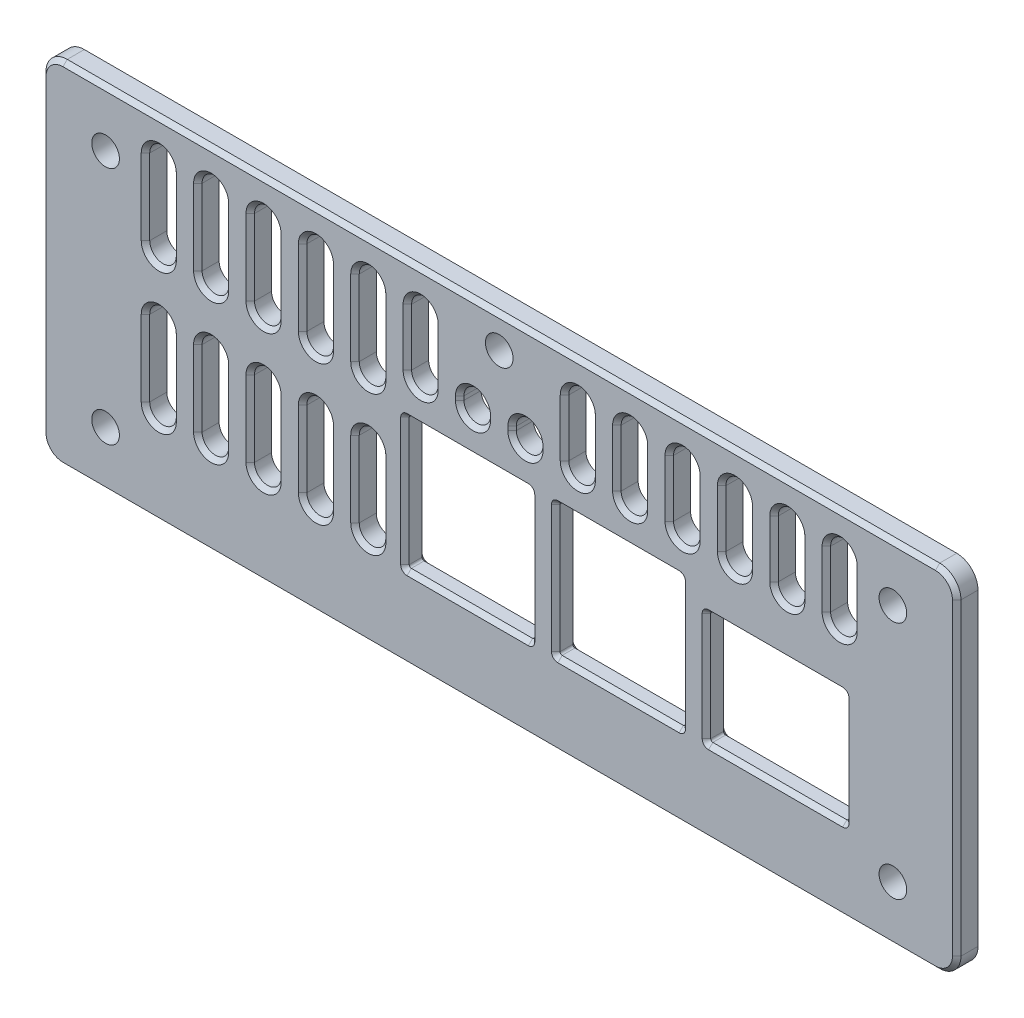
SolidWorks part; units mm, degrees
ref_plane "Plane XZ" through (0, 0, 0) normal (0, 0, 1) x (1, 0, 0)
ref_plane "Plane XY" through (0, 0, 0) normal (0, 1, 0) x (1, 0, 0)
ref_plane "Plane YZ" through (0, 0, 0) normal (1, 0, 0) x (0, 0, -1)
sketch "Sketch1" plane through (0, 0, 0) normal (0, 0, 1) x (1, 0, 0)
  line L0 (-55.88, -14.2875) -> (55.88, -14.2875) construction
  line L1 (-55.88, 22.225) -> (55.88, 22.225) construction
  line L2 (-55.88, 22.225) -> (-55.88, -22.225) construction
  line L3 (-55.88, -22.225) -> (55.88, -22.225) construction
  line L4 (55.88, 22.225) -> (55.88, -22.225) construction
  line L5 (0, 0) -> (0, -14.2875) construction
  line L6 (0, 0) -> (-55.88, 0) construction
  line L7 (-54.61, 20.955) -> (54.61, 20.955)
  line L8 (54.61, 20.955) -> (54.61, -20.955)
  line L9 (-54.61, -20.955) -> (54.61, -20.955)
  line L10 (-54.61, 20.955) -> (-54.61, -20.955)
  dimension "D1" = 111.76
  dimension "D2" = 44.45
  dimension "D3" = 14.2875
  dimension "D4" = 1.27
extrude "Boss-Extrude1" add sketch "Sketch1" along normal blind 2.54
sketch "Sketch4" plane through (0, 0, 2.54) normal (0, 0, 1) x (1, 0, 0)
  line L0 (-46.99, 0) -> (46.99, 0) construction
  line L1 (-46.99, 14.2875) -> (46.99, 14.2875) construction
  line L2 (-46.99, 14.2875) -> (-46.99, -14.2875) construction
  line L3 (-46.99, -14.2875) -> (46.99, -14.2875) construction
  line L4 (46.99, 14.2875) -> (46.99, -14.2875) construction
  circle A0 centre (-46.99, 14.2875) radius 1.651
  circle A1 centre (-46.99, -14.2875) radius 1.651
  circle A2 centre (46.99, -14.2875) radius 1.651
  circle A3 centre (46.99, 14.2875) radius 1.651
  dimension "D1" = 3.302
  dimension "D4" = 3.302
  dimension "D2" = 93.98
  dimension "D3" = 28.575
extrude "Cut-Extrude2" cut sketch "Sketch4" against normal through all and the other way through all
fillet "Fillet1" radius 2.54 4 edges at (54.61, 20.955, 1.27) (54.61, -20.955, 1.27) (-54.61, -20.955, 1.27) (-54.61, 20.955, 1.27)
sketch "Sketch3" plane through (0, 0, 2.54) normal (0, 0, 1) x (1, 0, 0)
  line L0 (15.24, -11.1252) -> (15.24, -12.3825) construction
  line L1 (-12.76, -11.1252) -> (43.24, -11.1252) construction
  line L2 (-12.76, -11.1252) -> (-12.76, -12.3825) construction
  line L3 (-12.76, -12.3825) -> (43.24, -12.3825) construction
  line L4 (43.24, -11.1252) -> (43.24, -12.3825) construction
  line L5 (-55.88, -14.2875) -> (55.88, -14.2875) construction
  line L6 (-3.76, 4.6228) -> (-3.76, -11.1252) construction
  line L7 (-11.253, 4.6228) -> (3.733, 4.6228)
  line L8 (-11.253, 4.6228) -> (-11.253, -11.1252)
  line L9 (-11.253, -11.1252) -> (3.733, -11.1252)
  line L10 (3.733, 4.6228) -> (3.733, -11.1252)
  line L11 (6.747, 4.6228) -> (21.733, 4.6228)
  line L12 (6.747, 4.6228) -> (6.747, -11.1252)
  line L13 (6.747, -11.1252) -> (21.733, -11.1252)
  line L14 (21.733, 4.6228) -> (21.733, -11.1252)
  line L15 (24.735, 2.3368) -> (41.245, 2.3368)
  line L16 (24.735, 2.3368) -> (24.735, -11.1252)
  line L17 (24.735, -11.1252) -> (41.245, -11.1252)
  line L18 (41.245, 2.3368) -> (41.245, -11.1252)
  line L19 (14.24, 4.6228) -> (14.24, -11.1252) construction
  line L20 (32.99, 2.3368) -> (32.99, -11.1252) construction
  dimension "D1" = 15.24
  dimension "D2" = 1.905
  dimension "D3" = 1.2573
  dimension "D4" = 56
  dimension "D5" = 15.748
  dimension "D6" = 14.986
  dimension "D7" = 16.51
  dimension "D8" = 13.462
  dimension "D9" = 9
  dimension "D10" = 27
  dimension "D11" = 45.75
extrude "RPi 4 Cutout" cut sketch "Sketch3" against normal through all
sketch "Sketch14" plane through (0, 0, 2.54) normal (0, 0, 1) x (1, 0, 0)
  circle A0 centre (0, 17.145) radius 1.651
  dimension "D2" = 3.302
  dimension "D1" = 17.145
extrude "Cut-Extrude8" cut sketch "Sketch14" against normal through all
sketch "Sketch15" plane through (0, 0, 2.54) normal (0, 0, 1) x (1, 0, 0)
  line L0 (40.64, 9.3853) -> (40.64, 16.1925) construction
  line L1 (54.61, 0) -> (50.3635, 0) construction
  line L2 (50.3635, -17.78) -> (-15.1531, -17.78) construction
  line L3 (50.3635, -17.78) -> (50.3635, 17.78) construction
  line L4 (50.3635, 17.78) -> (-15.1531, 17.78) construction
  line L5 (-15.1531, -17.78) -> (-15.1531, 17.78) construction
  line L6 (54.61, -18.415) -> (54.61, 18.415) construction
  line L7 (39.0525, 9.3853) -> (39.0525, 16.1925)
  line L8 (42.2275, 9.3853) -> (42.2275, 16.1925)
  line L9 (-15.1531, 7.7978) -> (50.3635, 7.7978) construction
  line L10 (21.733, 4.6228) -> (6.747, 4.6228) construction
  line L11 (34.3877, 9.3853) -> (34.3877, 16.1925) construction
  line L12 (32.8002, 9.3853) -> (32.8002, 16.1925)
  line L13 (35.9752, 9.3853) -> (35.9752, 16.1925)
  line L14 (28.1354, 9.3853) -> (28.1354, 16.1925) construction
  line L15 (26.5479, 9.3853) -> (26.5479, 16.1925)
  line L16 (29.7229, 9.3853) -> (29.7229, 16.1925)
  line L17 (21.8831, 9.3853) -> (21.8831, 16.1925) construction
  line L18 (20.2956, 9.3853) -> (20.2956, 16.1925)
  line L19 (23.4706, 9.3853) -> (23.4706, 16.1925)
  line L20 (15.6308, 9.3853) -> (15.6308, 16.1925) construction
  line L21 (14.0433, 9.3853) -> (14.0433, 16.1925)
  line L22 (17.2183, 9.3853) -> (17.2183, 16.1925)
  line L23 (9.3785, 9.3853) -> (9.3785, 16.1925) construction
  line L24 (7.791, 9.3853) -> (7.791, 16.1925)
  line L25 (10.966, 9.3853) -> (10.966, 16.1925)
  line L26 (3.1262, 9.3853) -> (3.1262, 16.1925) construction
  line L27 (1.5387, 9.3853) -> (1.5387, 16.1925) construction
  line L28 (4.7137, 9.3853) -> (4.7137, 16.1925) construction
  line L29 (-3.1262, 9.3853) -> (-3.1262, 16.1925) construction
  line L30 (-4.7137, 9.3853) -> (-4.7137, 16.1925) construction
  line L31 (-1.5387, 9.3853) -> (-1.5387, 16.1925) construction
  line L32 (-9.3785, 9.3853) -> (-9.3785, 16.1925) construction
  line L33 (-10.966, 9.3853) -> (-10.966, 16.1925)
  line L34 (-7.791, 9.3853) -> (-7.791, 16.1925)
  line L35 (-3.1262, 9.3853) -> (-3.1262, 9.849) construction
  line L36 (-4.7137, 9.3853) -> (-4.7137, 9.849)
  line L37 (-1.5387, 9.3853) -> (-1.5387, 9.849)
  line L38 (3.1262, 9.3853) -> (3.1262, 9.849) construction
  line L39 (1.5387, 9.3853) -> (1.5387, 9.849)
  line L40 (4.7137, 9.3853) -> (4.7137, 9.849)
  line L41 (-15.6308, 9.3853) -> (-15.6308, 16.1925) construction
  line L42 (-17.2183, 9.3853) -> (-17.2183, 16.1925)
  line L43 (-14.0433, 9.3853) -> (-14.0433, 16.1925)
  line L44 (-21.8831, 9.3853) -> (-21.8831, 16.1925) construction
  line L45 (-23.4706, 9.3853) -> (-23.4706, 16.1925)
  line L46 (-20.2956, 9.3853) -> (-20.2956, 16.1925)
  line L47 (-28.1354, 9.3853) -> (-28.1354, 16.1925) construction
  line L48 (-29.7229, 9.3853) -> (-29.7229, 16.1925)
  line L49 (-26.5479, 9.3853) -> (-26.5479, 16.1925)
  line L50 (-34.3877, 9.3853) -> (-34.3877, 16.1925) construction
  line L51 (-35.9752, 9.3853) -> (-35.9752, 16.1925)
  line L52 (-32.8002, 9.3853) -> (-32.8002, 16.1925)
  line L53 (-40.64, 9.3853) -> (-40.64, 16.1925) construction
  line L54 (-42.2275, 9.3853) -> (-42.2275, 16.1925)
  line L55 (-39.0525, 9.3853) -> (-39.0525, 16.1925)
  circle A0 centre (46.99, 14.2875) radius 4.7625 construction
  arc A1 (39.0525, 9.3853) -> (42.2275, 9.3853) centre (40.64, 9.3853) ccw
  arc A2 (42.2275, 16.1925) -> (39.0525, 16.1925) centre (40.64, 16.1925) ccw
  arc A3 (32.8002, 9.3853) -> (35.9752, 9.3853) centre (34.3877, 9.3853) ccw
  arc A4 (35.9752, 16.1925) -> (32.8002, 16.1925) centre (34.3877, 16.1925) ccw
  arc A5 (26.5479, 9.3853) -> (29.7229, 9.3853) centre (28.1354, 9.3853) ccw
  arc A6 (29.7229, 16.1925) -> (26.5479, 16.1925) centre (28.1354, 16.1925) ccw
  arc A7 (20.2956, 9.3853) -> (23.4706, 9.3853) centre (21.8831, 9.3853) ccw
  arc A8 (23.4706, 16.1925) -> (20.2956, 16.1925) centre (21.8831, 16.1925) ccw
  arc A9 (14.0433, 9.3853) -> (17.2183, 9.3853) centre (15.6308, 9.3853) ccw
  arc A10 (17.2183, 16.1925) -> (14.0433, 16.1925) centre (15.6308, 16.1925) ccw
  arc A11 (7.791, 9.3853) -> (10.966, 9.3853) centre (9.3785, 9.3853) ccw
  arc A12 (10.966, 16.1925) -> (7.791, 16.1925) centre (9.3785, 16.1925) ccw
  arc A13 (1.5387, 9.3853) -> (4.7137, 9.3853) centre (3.1262, 9.3853) ccw construction
  arc A14 (4.7137, 16.1925) -> (1.5387, 16.1925) centre (3.1262, 16.1925) ccw construction
  arc A15 (-4.7137, 9.3853) -> (-1.5387, 9.3853) centre (-3.1262, 9.3853) ccw construction
  arc A16 (-1.5387, 16.1925) -> (-4.7137, 16.1925) centre (-3.1262, 16.1925) ccw construction
  arc A17 (-10.966, 9.3853) -> (-7.791, 9.3853) centre (-9.3785, 9.3853) ccw
  arc A18 (-7.791, 16.1925) -> (-10.966, 16.1925) centre (-9.3785, 16.1925) ccw
  circle A19 centre (0, 17.145) radius 6.35 construction
  arc A20 (-4.7137, 9.3853) -> (-1.5387, 9.3853) centre (-3.1262, 9.3853) ccw
  arc A21 (-1.5387, 9.849) -> (-4.7137, 9.849) centre (-3.1262, 9.849) ccw
  arc A22 (1.5387, 9.3853) -> (4.7137, 9.3853) centre (3.1262, 9.3853) ccw
  arc A23 (4.7137, 9.849) -> (1.5387, 9.849) centre (3.1262, 9.849) ccw
  circle A24 centre (-46.99, 14.2875) radius 4.7625 construction
  arc A25 (-17.2183, 9.3853) -> (-14.0433, 9.3853) centre (-15.6308, 9.3853) ccw
  arc A26 (-14.0433, 16.1925) -> (-17.2183, 16.1925) centre (-15.6308, 16.1925) ccw
  arc A27 (-23.4706, 9.3853) -> (-20.2956, 9.3853) centre (-21.8831, 9.3853) ccw
  arc A28 (-20.2956, 16.1925) -> (-23.4706, 16.1925) centre (-21.8831, 16.1925) ccw
  arc A29 (-29.7229, 9.3853) -> (-26.5479, 9.3853) centre (-28.1354, 9.3853) ccw
  arc A30 (-26.5479, 16.1925) -> (-29.7229, 16.1925) centre (-28.1354, 16.1925) ccw
  arc A31 (-35.9752, 9.3853) -> (-32.8002, 9.3853) centre (-34.3877, 9.3853) ccw
  arc A32 (-32.8002, 16.1925) -> (-35.9752, 16.1925) centre (-34.3877, 16.1925) ccw
  arc A33 (-42.2275, 9.3853) -> (-39.0525, 9.3853) centre (-40.64, 9.3853) ccw
  arc A34 (-39.0525, 16.1925) -> (-42.2275, 16.1925) centre (-40.64, 16.1925) ccw
  point P13 (40.64, 12.7889)
  point P25 (34.3877, 12.7889)
  point P32 (28.1354, 12.7889)
  point P39 (21.8831, 12.7889)
  point P46 (15.6308, 12.7889)
  point P53 (9.3785, 12.7889)
  point P60 (3.1262, 12.7889)
  point P67 (-3.1262, 12.7889)
  point P74 (-9.3785, 12.7889)
  point P83 (-3.1262, 9.6172)
  point P88 (3.1262, 9.6172)
  point P100 (-15.6308, 12.7889)
  point P107 (-21.8831, 12.7889)
  point P114 (-28.1354, 12.7889)
  point P121 (-34.3877, 12.7889)
  point P128 (-40.64, 12.7889)
  dimension "D1" = 9.525
  dimension "D7" = 12.7
  dimension "D2" = 35.56
  dimension "D3" = 3.175
  dimension "D4" = 3.175
  dimension "D5" = 14
extrude "Cut-Extrude9" cut sketch "Sketch15" against normal through all
sketch "Sketch22" plane through (0, 0, 2.54) normal (0, 0, 1) x (1, 0, 0)
  line L0 (-54.61, 3.3274) -> (-18.7557, 3.3274) construction
  line L1 (-54.61, 18.415) -> (-54.61, -18.415) construction
  line L2 (-11.253, -11.1252) -> (-54.61, -11.1252) construction
  line L3 (-40.64, 16.1925) -> (-40.64, 7.1374) construction
  line L4 (-39.0525, 16.1925) -> (-39.0525, 7.1374)
  line L5 (-42.2275, 16.1925) -> (-42.2275, 7.1374)
  line L6 (-40.64, -0.4826) -> (-40.64, -9.5377) construction
  line L7 (-39.0525, -0.4826) -> (-39.0525, -9.5377)
  line L8 (-42.2275, -0.4826) -> (-42.2275, -9.5377)
  line L9 (-34.3877, 16.1925) -> (-34.3877, 7.1374) construction
  line L10 (-32.8002, 16.1925) -> (-32.8002, 7.1374)
  line L11 (-35.9752, 16.1925) -> (-35.9752, 7.1374)
  line L12 (-34.3877, -0.4826) -> (-34.3877, -9.5377) construction
  line L13 (-32.8002, -0.4826) -> (-32.8002, -9.5377)
  line L14 (-35.9752, -0.4826) -> (-35.9752, -9.5377)
  line L15 (-28.1354, 16.1925) -> (-28.1354, 7.1374) construction
  line L16 (-26.5479, 16.1925) -> (-26.5479, 7.1374)
  line L17 (-29.7229, 16.1925) -> (-29.7229, 7.1374)
  line L18 (-28.1354, -0.4826) -> (-28.1354, -9.5377) construction
  line L19 (-26.5479, -0.4826) -> (-26.5479, -9.5377)
  line L20 (-29.7229, -0.4826) -> (-29.7229, -9.5377)
  line L21 (-21.8831, 16.1925) -> (-21.8831, 7.1374) construction
  line L22 (-20.2956, 16.1925) -> (-20.2956, 7.1374)
  line L23 (-23.4706, 16.1925) -> (-23.4706, 7.1374)
  line L24 (-21.8831, -0.4826) -> (-21.8831, -9.5377) construction
  line L25 (-20.2956, -0.4826) -> (-20.2956, -9.5377)
  line L26 (-23.4706, -0.4826) -> (-23.4706, -9.5377)
  line L27 (-15.6308, 16.1925) -> (-15.6308, 7.1374) construction
  line L28 (-14.0433, 16.1925) -> (-14.0433, 7.1374)
  line L29 (-17.2183, 16.1925) -> (-17.2183, 7.1374)
  line L30 (-15.6308, -0.4826) -> (-15.6308, -9.5377) construction
  line L31 (-14.0433, -0.4826) -> (-14.0433, -9.5377)
  line L32 (-17.2183, -0.4826) -> (-17.2183, -9.5377)
  arc A0 (-39.0525, 16.1925) -> (-42.2275, 16.1925) centre (-40.64, 16.1925) ccw
  arc A1 (-42.2275, 7.1374) -> (-39.0525, 7.1374) centre (-40.64, 7.1374) ccw
  arc A2 (-39.0525, -0.4826) -> (-42.2275, -0.4826) centre (-40.64, -0.4826) ccw
  arc A3 (-42.2275, -9.5377) -> (-39.0525, -9.5377) centre (-40.64, -9.5377) ccw
  arc A4 (-39.0525, 16.1925) -> (-42.2275, 16.1925) centre (-40.64, 16.1925) ccw construction
  arc A5 (-32.8002, 16.1925) -> (-35.9752, 16.1925) centre (-34.3877, 16.1925) ccw
  arc A6 (-35.9752, 7.1374) -> (-32.8002, 7.1374) centre (-34.3877, 7.1374) ccw
  arc A7 (-32.8002, -0.4826) -> (-35.9752, -0.4826) centre (-34.3877, -0.4826) ccw
  arc A8 (-35.9752, -9.5377) -> (-32.8002, -9.5377) centre (-34.3877, -9.5377) ccw
  arc A9 (-26.5479, 16.1925) -> (-29.7229, 16.1925) centre (-28.1354, 16.1925) ccw
  arc A10 (-29.7229, 7.1374) -> (-26.5479, 7.1374) centre (-28.1354, 7.1374) ccw
  arc A11 (-26.5479, -0.4826) -> (-29.7229, -0.4826) centre (-28.1354, -0.4826) ccw
  arc A12 (-29.7229, -9.5377) -> (-26.5479, -9.5377) centre (-28.1354, -9.5377) ccw
  arc A13 (-20.2956, 16.1925) -> (-23.4706, 16.1925) centre (-21.8831, 16.1925) ccw
  arc A14 (-23.4706, 7.1374) -> (-20.2956, 7.1374) centre (-21.8831, 7.1374) ccw
  arc A15 (-20.2956, -0.4826) -> (-23.4706, -0.4826) centre (-21.8831, -0.4826) ccw
  arc A16 (-23.4706, -9.5377) -> (-20.2956, -9.5377) centre (-21.8831, -9.5377) ccw
  arc A17 (-14.0433, 16.1925) -> (-17.2183, 16.1925) centre (-15.6308, 16.1925) ccw
  arc A18 (-17.2183, 7.1374) -> (-14.0433, 7.1374) centre (-15.6308, 7.1374) ccw
  arc A19 (-14.0433, -0.4826) -> (-17.2183, -0.4826) centre (-15.6308, -0.4826) ccw
  arc A20 (-17.2183, -9.5377) -> (-14.0433, -9.5377) centre (-15.6308, -9.5377) ccw
  arc A21 (-32.8002, 16.1925) -> (-35.9752, 16.1925) centre (-34.3877, 16.1925) ccw construction
  point P9 (-40.64, 11.6649)
  point P14 (-40.64, -5.0102)
  point P26 (-34.3877, 11.6649)
  point P32 (-34.3877, -5.0102)
  point P41 (-28.1354, 11.6649)
  point P46 (-28.1354, -5.0102)
  point P55 (-21.8831, 11.6649)
  point P60 (-21.8831, -5.0102)
  point P69 (-15.6308, 11.6649)
  point P74 (-15.6308, -5.0102)
  dimension "D1" = 3.81
  dimension "D2" = 5
extrude "Cut-Extrude15" cut sketch "Sketch22" against normal through all
fillet "Fillet3" radius 0.254 12 edges at (3.733, 4.6228, 1.27) (21.733, 4.6228, 1.27) (3.733, -11.1252, 1.27) (21.733, -11.1252, 1.27) (-11.253, -11.1252, 1.27) (6.747, -11.1252, 1.27) (24.735, -11.1252, 1.27) (-11.253, 4.6228, 1.27) (6.747, 4.6228, 1.27) (24.735, 2.3368, 1.27) (41.245, 2.3368, 1.27) (41.245, -11.1252, 1.27)
chamfer "Chamfer2" distance 0.508 angle 45 24 edges at (-3.76, -11.1252, 0) (3.6586, -11.0508, 0) (-11.1786, -11.0508, 0) (3.733, -3.2512, 0) (-11.253, -3.2512, 0) (3.6586, 4.5484, 0) (-11.1786, 4.5484, 0) (-3.76, 4.6228, 0) (14.24, -11.1252, 0) (21.6586, -11.0508, 0) (6.8214, -11.0508, 0) (21.733, -3.2512, 0) (6.747, -3.2512, 0) (21.6586, 4.5484, 0) (6.8214, 4.5484, 0) (14.24, 4.6228, 0) (32.99, -11.1252, 0) (41.1706, -11.0508, 0) (24.8094, -11.0508, 0) (41.245, -4.3942, 0) (24.735, -4.3942, 0) (41.1706, 2.2624, 0) (24.8094, 2.2624, 0) (32.99, 2.3368, 0)
chamfer "Chamfer3" distance 0.508 angle 45 108 edges at (-34.3877, -11.1252, 2.54) (-32.8002, -5.0102, 2.54) (-35.9752, -5.0102, 2.54) (-34.3877, 1.1049, 2.54) (-28.1354, -11.1252, 2.54) (-26.5479, -5.0102, 2.54) (-29.7229, -5.0102, 2.54) (-28.1354, 1.1049, 2.54) (-21.8831, -11.1252, 2.54) (-20.2956, -5.0102, 2.54) (-23.4706, -5.0102, 2.54) (-21.8831, 1.1049, 2.54) (-15.6308, -11.1252, 2.54) (-14.0433, -5.0102, 2.54) (-17.2183, -5.0102, 2.54) (-15.6308, 1.1049, 2.54) (-3.76, -11.1252, 2.54) (3.6586, -11.0508, 2.54) (-11.1786, -11.0508, 2.54) (3.733, -3.2512, 2.54) (-11.253, -3.2512, 2.54) (3.6586, 4.5484, 2.54) (-11.1786, 4.5484, 2.54) (-3.76, 4.6228, 2.54) (14.24, -11.1252, 2.54) (21.6586, -11.0508, 2.54) (6.8214, -11.0508, 2.54) (21.733, -3.2512, 2.54) (6.747, -3.2512, 2.54) (21.6586, 4.5484, 2.54) (6.8214, 4.5484, 2.54) (14.24, 4.6228, 2.54) (32.99, -11.1252, 2.54) (41.1706, -11.0508, 2.54) (24.8094, -11.0508, 2.54) (41.245, -4.3942, 2.54) (24.735, -4.3942, 2.54) (41.1706, 2.2624, 2.54) (24.8094, 2.2624, 2.54) (32.99, 2.3368, 2.54) (40.64, 7.7978, 2.54) (42.2275, 12.7889, 2.54) (39.0525, 12.7889, 2.54) (40.64, 17.78, 2.54) (34.3877, 7.7978, 2.54) (35.9752, 12.7889, 2.54) (32.8002, 12.7889, 2.54) (34.3877, 17.78, 2.54) (28.1354, 7.7978, 2.54) (29.7229, 12.7889, 2.54) (26.5479, 12.7889, 2.54) (28.1354, 17.78, 2.54) (21.8831, 7.7978, 2.54) (23.4706, 12.7889, 2.54) (20.2956, 12.7889, 2.54) (21.8831, 17.78, 2.54) (15.6308, 7.7978, 2.54) (17.2183, 12.7889, 2.54) (14.0433, 12.7889, 2.54) (15.6308, 17.78, 2.54) (9.3785, 7.7978, 2.54) (10.966, 12.7889, 2.54) (7.791, 12.7889, 2.54) (9.3785, 17.78, 2.54) (3.1262, 7.7978, 2.54) (4.7137, 9.6172, 2.54) (1.5387, 9.6172, 2.54) (3.1262, 11.4365, 2.54) (-3.1262, 7.7978, 2.54) (-1.5387, 9.6172, 2.54) (-4.7137, 9.6172, 2.54) (-3.1262, 11.4365, 2.54) (-9.3785, 7.7978, 2.54) (-7.791, 12.7889, 2.54) (-10.966, 12.7889, 2.54) (-9.3785, 17.78, 2.54) (-15.6308, 5.5499, 2.54) (-14.0433, 11.6649, 2.54) (-17.2183, 11.6649, 2.54) (-15.6308, 17.78, 2.54) (-21.8831, 5.5499, 2.54) (-20.2956, 11.6649, 2.54) (-23.4706, 11.6649, 2.54) (-21.8831, 17.78, 2.54) (-28.1354, 5.5499, 2.54) (-26.5479, 11.6649, 2.54) (-29.7229, 11.6649, 2.54) (-28.1354, 17.78, 2.54) (-34.3877, 5.5499, 2.54) (-32.8002, 11.6649, 2.54) (-35.9752, 11.6649, 2.54) (-34.3877, 17.78, 2.54) (-40.64, 5.5499, 2.54) (-39.0525, 11.6649, 2.54) (-42.2275, 11.6649, 2.54) (-40.64, 17.78, 2.54) (-40.64, -11.1252, 2.54) (-39.0525, -5.0102, 2.54) (-42.2275, -5.0102, 2.54) (-40.64, 1.1049, 2.54) (0, 20.955, 2.54) (-53.8661, 20.2111, 2.54) (53.8661, 20.2111, 2.54) (-54.61, 0, 2.54) (54.61, 0, 2.54) (-53.8661, -20.2111, 2.54) (53.8661, -20.2111, 2.54) (0, -20.955, 2.54)
